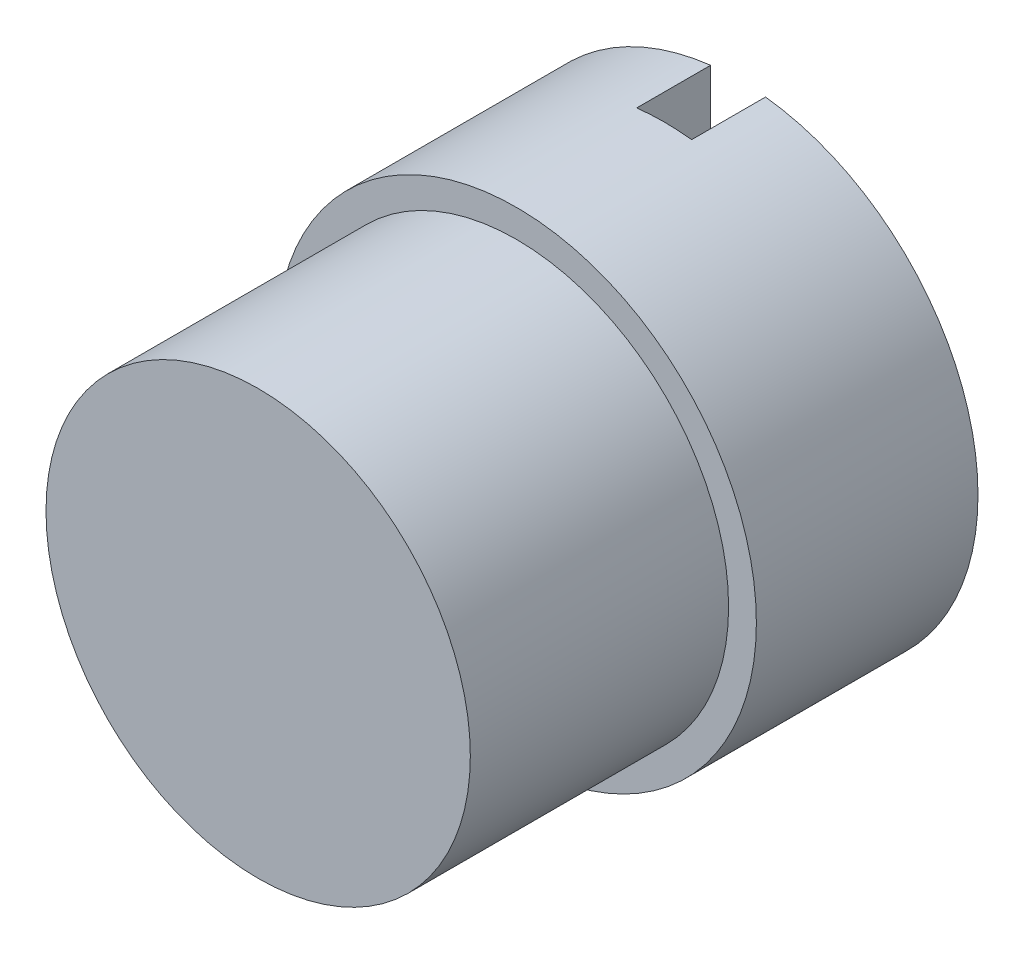
SolidWorks part; units mm, degrees
ref_plane "Front Plane" through (0, 0, 0) normal (0, 0, 1) x (1, 0, 0)
ref_plane "Top Plane" through (0, 0, 0) normal (0, 1, 0) x (1, 0, 0)
ref_plane "Right Plane" through (0, 0, 0) normal (1, 0, 0) x (0, 0, -1)
sketch "Sketch1" plane through (0, 0, 0) normal (0, 0, 1) x (1, 0, 0)
  circle A0 centre (0, 0) radius 6.5405
  circle A1 centre (0, 0) radius 10.3124
  dimension "D1" = 13.081
  dimension "D2" = 20.6248
extrude "Boss-Extrude1" add sketch "Sketch1" against normal blind 9.525
cosmetic thread "Cosmetic Thread1" parameters "D1"=9.525, "D2"=19.3802
sketch "Sketch2" plane through (0, 0, 0) normal (0, 0, 1) x (1, 0, 0)
  circle A0 centre (0, 0) radius 9.1186
  dimension "D1" = 18.2372
extrude "Boss-Extrude2" add sketch "Sketch2" along normal blind 11.0998
sketch "Sketch3" plane through (0, 0, 0) normal (0, 1, 0) x (1, 0, 0)
  line L0 (0, 0) -> (0, 9.525) construction
  line L1 (10.3124, 9.525) -> (-10.3124, 9.525) construction
  line L3 (-1.1811, 9.525) -> (1.1811, 9.525)
  line L4 (-1.1811, 9.525) -> (-1.1811, 6.35)
  line L5 (-1.1811, 6.35) -> (1.1811, 6.35)
  line L6 (1.1811, 9.525) -> (1.1811, 6.35)
  dimension "D1" = 2.3622
  dimension "D2" = 3.175
extrude "Cut-Extrude1" cut sketch "Sketch3" against normal through all both and the other way through all
